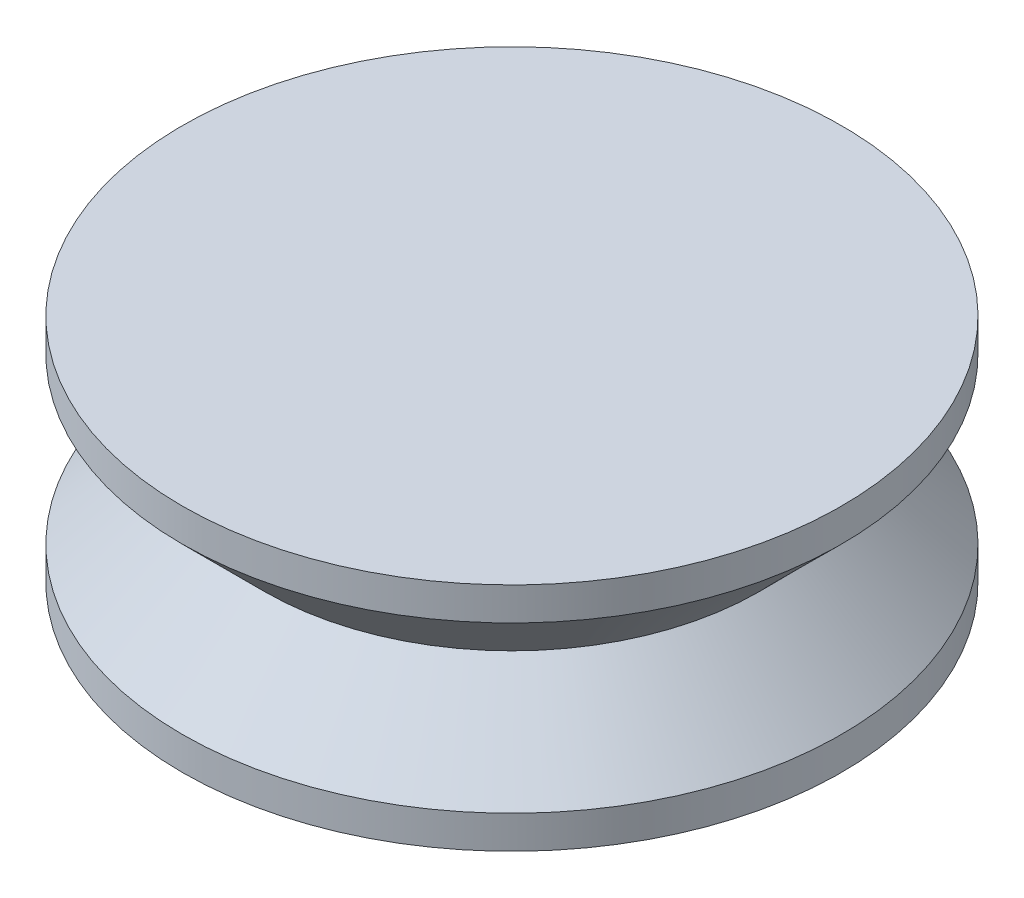
SolidWorks part; units mm, degrees
ref_plane "Front Plane" through (0, 0, 0) normal (0, 0, 1) x (1, 0, 0)
ref_plane "Top Plane" through (0, 0, 0) normal (0, 1, 0) x (1, 0, 0)
ref_plane "Right Plane" through (0, 0, 0) normal (1, 0, 0) x (0, 0, -1)
sketch "Sketch2" plane through (0, 0, 0) normal (0, 0, 1) x (1, 0, 0)
  line L0 (0, 4.445) -> (0, -4.445)
  line L1 (0, -4.445) -> (12.7, -4.445)
  line L2 (12.7, -4.445) -> (12.7, -3.175)
  line L3 (12.7, -3.175) -> (9.525, 0)
  line L4 (9.525, 0) -> (12.7, 3.175)
  line L5 (12.7, 3.175) -> (12.7, 4.445)
  line L6 (12.7, 4.445) -> (0, 4.445)
  point P12 (0, 0)
  dimension "D1" = 3.175
  dimension "D2" = 12.7
  dimension "D3" = 6.35
  dimension "D4" = 8.89
revolve "Revolve1" add sketch "Sketch2" angle 360 about L0
